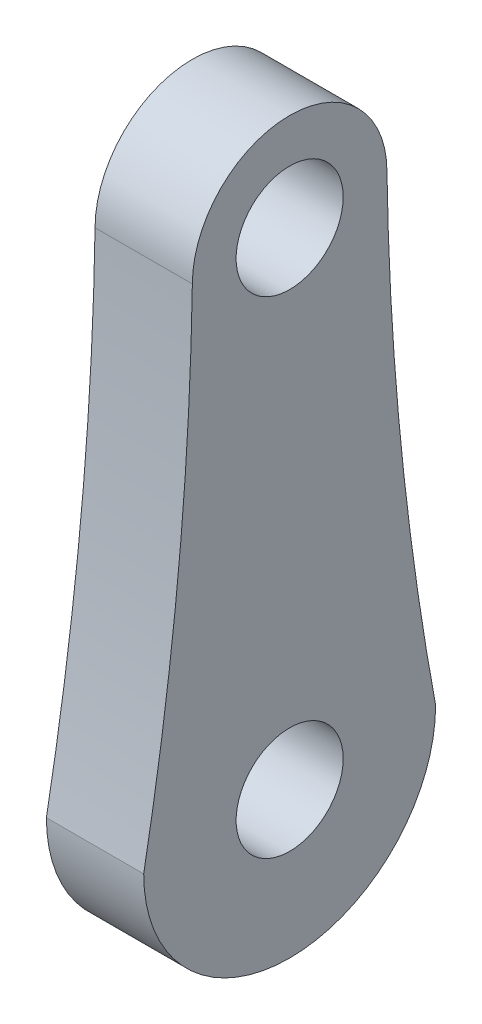
SolidWorks part; units mm, degrees
ref_plane "정면" through (0, 0, 0) normal (0, 0, 1) x (1, 0, 0)
ref_plane "윗면" through (0, 0, 0) normal (0, 1, 0) x (1, 0, 0)
ref_plane "우측면" through (0, 0, 0) normal (1, 0, 0) x (0, 0, -1)
sketch "Sketch1" plane through (0, 0, 0) normal (1, 0, 0) x (0, 0, -1)
  circle A0 centre (0, 0) radius 15
  circle A1 centre (0, 50) radius 10
  arc A2 (-10, 50) -> (-15, 0) centre (-309.9625, 54.7462) cw
  arc A3 (10, 50) -> (15, 0) centre (309.9625, 54.7462) ccw
  point P11 (0, 0)
  dimension "D1" = 30
  dimension "D2" = 20
  dimension "D3" = 300
  dimension "D4" = 300
  dimension "D5" = 50
extrude "Boss-Extrude1" add sketch "Sketch1" along normal blind 10 contours A3 A1 A2 A0 | A1 | A3 A0 A2
hole_wizard "M10 Clearance Hole1" positions "3DSketch2" profile "Sketch3" hole size "M10" standard "Ansi Metric" end condition through all
sketch3d "3DSketch2"
  line L0 (10, 50, 0) -> (0, 50, 0) construction
  arc A0 (10, 0, 15) -> (10, 0, -15) centre (10, 0, 0) ccw construction
  point P0 (0, 0, 0)
  point P3 (0, 0, 0)
  point P5 (0, 0, 0)
  point P7 (0, 0, 0)
  point P9 (10, 0, 0)
  point P16 (25, 0, 0)
  point P17 (10, 50, 0)
sketch "Sketch3" plane through (10, 50, 0) normal (0, 1, 0) x (0, 0, -1)
  line L0 (0, 0) -> (0, 10)
  line L1 (0, 10) -> (5.5, 10)
  line L2 (5.5, 10) -> (5.5, 0)
  line L5 (5.5, 0) -> (0, 0)
  line L11 (0, -6.35) -> (0, 107.95) construction
  dimension "관통 구멍 지름" = 11
  dimension "관통 구멍 깊이" = 10
